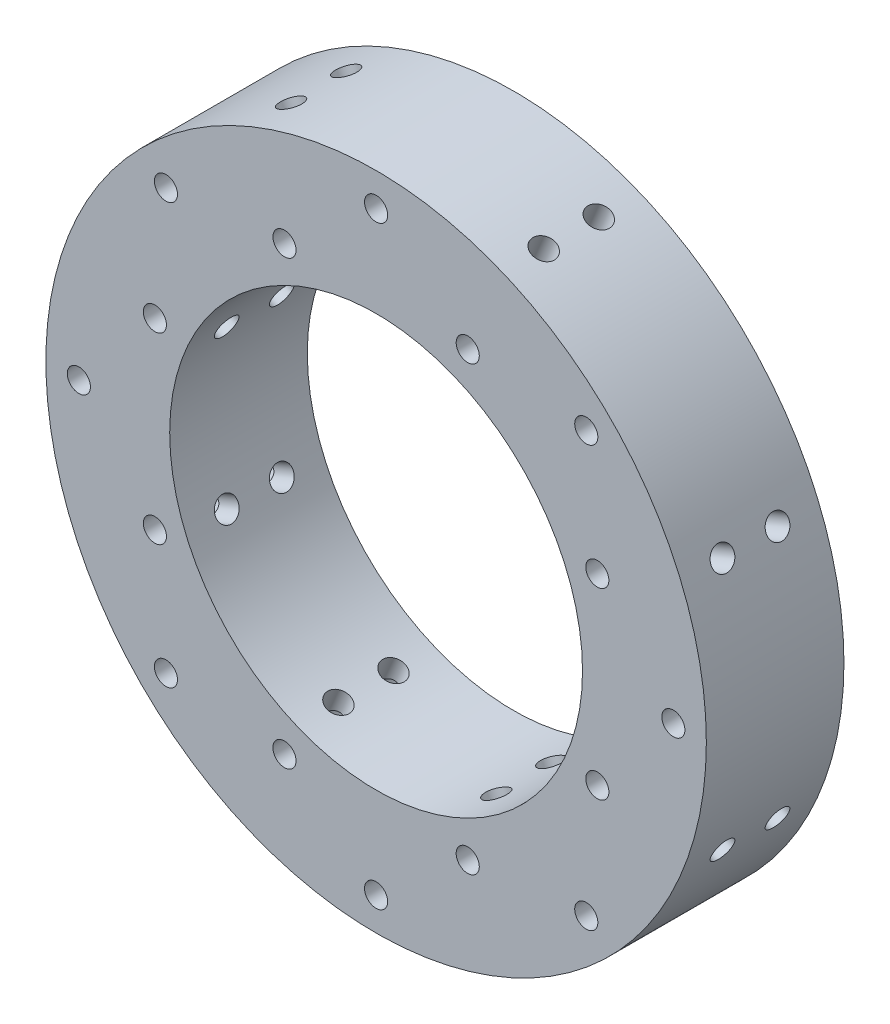
SolidWorks part; units mm, degrees
material "6061-T6 (SS)"
ref_plane "Front Plane" through (0, 0, 0) normal (0, 0, 1) x (1, 0, 0)
ref_plane "Top Plane" through (0, 0, 0) normal (0, 1, 0) x (1, 0, 0)
ref_plane "Right Plane" through (0, 0, 0) normal (1, 0, 0) x (0, 0, -1)
sketch "Sketch5" plane through (0, 0, 0) normal (0, 1, 0) x (1, 0, 0)
  line L0 (0, -16.5008) -> (0, 15.0181) construction
ref_plane "Plane1" through (0, 0, 0) normal (-0.3827, 0.9239, 0) x (0, 0, -1)
sketch "Sketch2" plane through (0, 0, 0) normal (0, 0, 1) x (1, 0, 0)
  line L0 (0, 0) -> (0, 60) construction
  line L2 (0, 0) -> (20.6649, 49.8895) construction
  circle A0 centre (0, 0) radius 37.5
  circle A1 centre (0, 0) radius 60
  circle A2 centre (0, 54) radius 2.1
  circle A3 centre (38.1838, 38.1838) radius 2.1
  circle A4 centre (54, 0) radius 2.1
  circle A5 centre (38.1838, -38.1838) radius 2.1
  circle A6 centre (0, -54) radius 2.1
  circle A7 centre (-38.1838, -38.1838) radius 2.1
  circle A8 centre (-54, 0) radius 2.1
  circle A9 centre (-38.1838, 38.1838) radius 2.1
  circle A11 centre (0, 0) radius 54 construction
  circle A12 centre (16.6467, 40.1888) radius 2.1
  circle A13 centre (40.1888, 16.6467) radius 2.1
  circle A14 centre (40.1888, -16.6467) radius 2.1
  circle A15 centre (16.6467, -40.1888) radius 2.1
  circle A16 centre (-16.6467, -40.1888) radius 2.1
  circle A17 centre (-40.1888, -16.6467) radius 2.1
  circle A18 centre (-40.1888, 16.6467) radius 2.1
  circle A19 centre (-16.6467, 40.1888) radius 2.1
  point P24 (0, 0)
  point P43 (0, 0)
  dimension "D1" = 4.2
  dimension "D2" = 75
  dimension "D3" = 120
  dimension "D6" = 8
  dimension "D9" = 4.2
  dimension "D4" = 6
  dimension "D5" = 8
  dimension "D8" = 22.5
  dimension "D10" = 43.5
extrude "Boss-Extrude1" add sketch "Sketch2" along normal blind 25
sketch "Sketch4" plane through (0, 0, 0) normal (-0.3827, 0.9239, 0) x (0, 0, -1)
  line L0 (0, 0) -> (-25, 0) construction
  line L1 (0, -60) -> (0, 60) construction
  line L2 (-25, 60) -> (-25, -60) construction
  circle A2 centre (-7.5, 0) radius 2.1
  circle A3 centre (-17.5, 0) radius 2.1
  dimension "D1" = 4.2
  dimension "D2" = 7.5
  dimension "D4" = 4.2
  dimension "D3" = 7.5
extrude "Cut-Extrude1" cut sketch "Sketch4" against normal through all both and the other way through all
pattern_circular "CirPattern1" count 4 every 45 about axis through (0, 0, 25) along (0, 0, 1) of "Cut-Extrude1"
